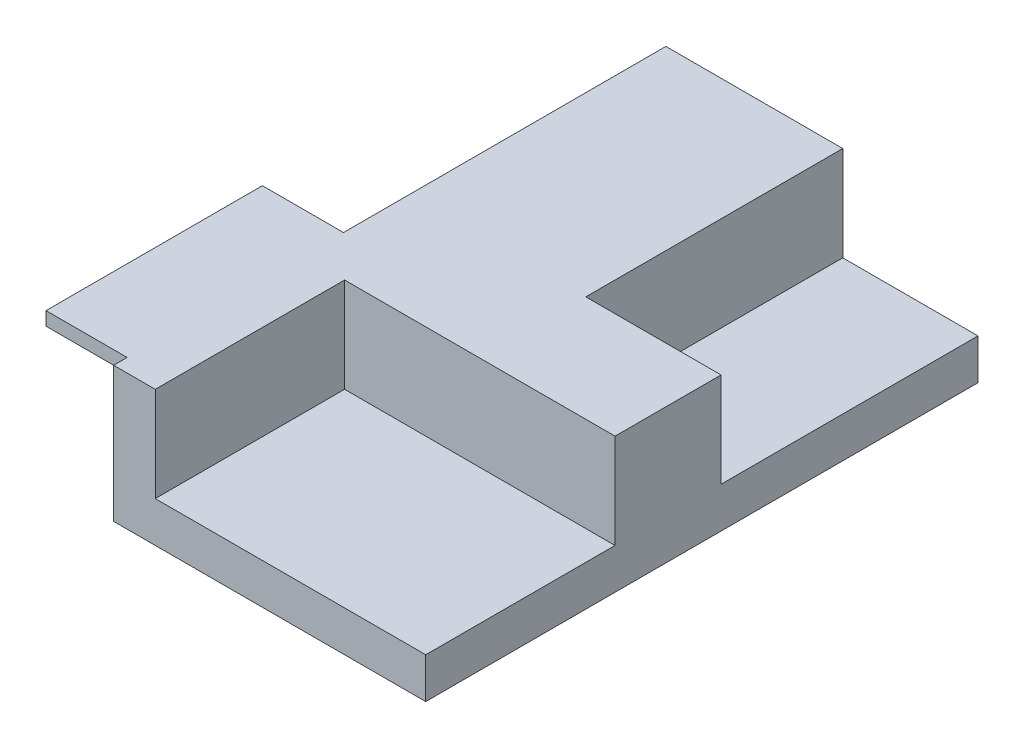
SolidWorks part; units mm, degrees
material "Polybutadiene (PB)"
ref_plane "Front Plane" through (0, 0, 0) normal (0, 0, 1) x (1, 0, 0)
ref_plane "Top Plane" through (0, 0, 0) normal (0, 1, 0) x (1, 0, 0)
ref_plane "Right Plane" through (0, 0, 0) normal (1, 0, 0) x (0, 0, -1)
sketch "MAINBODY_DWG" plane through (0, 0, 0) normal (0, 1, 0) x (1, 0, 0)
  line L1 (-11.54, -20.42) -> (11.54, -20.42)
  line L2 (-11.54, -20.42) -> (-11.54, 20.42)
  line L3 (-11.54, 20.42) -> (11.54, 20.42)
  line L4 (11.54, -20.42) -> (11.54, 20.42)
  line L5 (-11.54, -20.42) -> (11.54, 20.42) construction
  line L6 (-11.54, 20.42) -> (11.54, -20.42) construction
  point P0 (0, 0)
  dimension "D1" = 23.08
  dimension "D2" = 40.84
extrude "MAIN_BODY" add sketch "MAINBODY_DWG" along normal blind 10
sketch "PINS_DWG" plane through (-11.54, 0, 0) normal (-1, 0, 0) x (0, 0, 1)
  line L0 (-20.42, 10) -> (20.42, 10) construction
  line L1 (3.42, 10) -> (19.42, 10)
  line L2 (3.42, 10) -> (3.42, 9)
  line L3 (3.42, 9) -> (19.42, 9)
  line L4 (19.42, 10) -> (19.42, 9)
  line L5 (20.42, 10) -> (20.42, 0) construction
  dimension "D1" = 1
  dimension "D2" = 1
  dimension "D3" = 16
extrude "PINS" add sketch "PINS_DWG" along normal blind 6
sketch "RELIEF_DWG" plane through (0, 10, 0) normal (0, 1, 0) x (1, 0, 0)
  line L1 (11.54, 20.42) -> (1.5389, 20.42)
  line L2 (11.54, 20.42) -> (11.54, 1.42)
  line L3 (11.54, 1.42) -> (1.5389, 1.42)
  line L4 (1.5389, 20.42) -> (1.5389, 1.42)
  line L5 (11.54, -20.42) -> (-8.46, -20.42)
  line L6 (11.54, -20.42) -> (11.54, -6.42)
  line L7 (11.54, -6.42) -> (-8.46, -6.42)
  line L8 (-8.46, -20.42) -> (-8.46, -6.42)
  dimension "D1" = 14
  dimension "D2" = 20
  dimension "D3" = 19
  dimension "D4" = 10.0011
extrude "RELIEF" cut sketch "RELIEF_DWG" against normal blind 7
